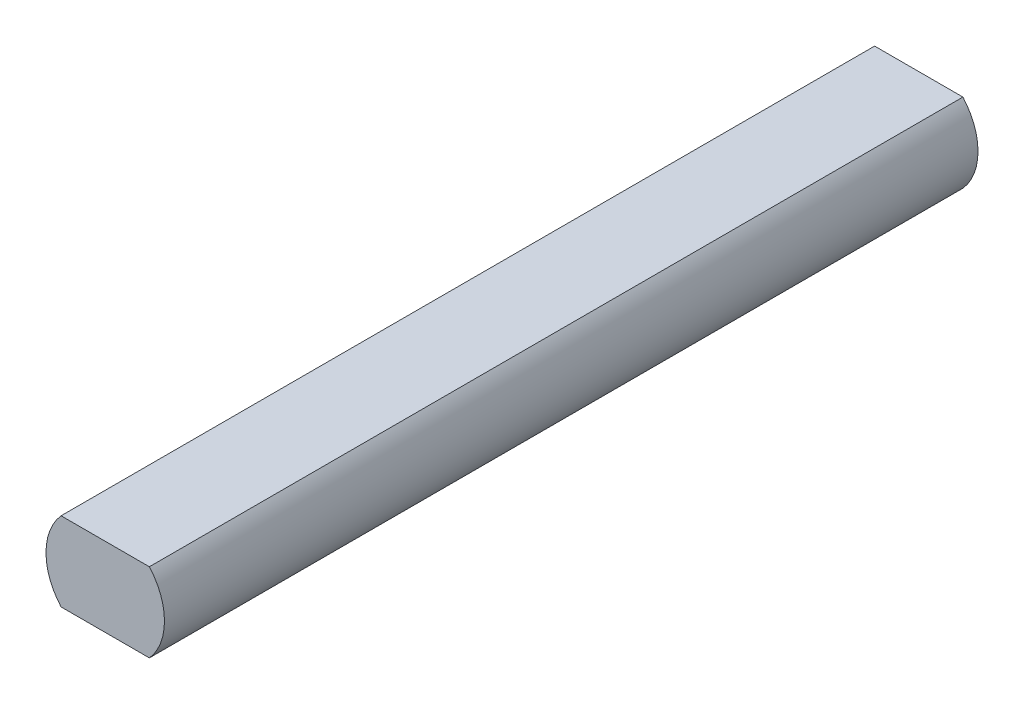
SolidWorks part; units mm, degrees
ref_plane "Front Plane" through (0, 0, 0) normal (0, 0, 1) x (1, 0, 0)
ref_plane "Top Plane" through (0, 0, 0) normal (0, 1, 0) x (1, 0, 0)
ref_plane "Right Plane" through (0, 0, 0) normal (1, 0, 0) x (0, 0, -1)
sketch "Sketch1" plane through (0, 0, 0) normal (0, 0, 1) x (1, 0, 0)
  line L0 (2.0092, 1.7967) -> (-2.0092, 1.7967)
  line L1 (-2.0092, -1.7967) -> (2.0092, -1.7967)
  arc A0 (-2.0092, -1.7967) -> (-2.0092, 1.7967) centre (0, 0) cw
  arc A1 (2.0092, 1.7967) -> (2.0092, -1.7967) centre (0, 0) cw
  circle A2 centre (0, 0) radius 2.6954 construction
  dimension "D2" = 5.3907
  dimension "D1" = 3.5933
extrude "Boss-Extrude1" add sketch "Sketch1" along normal mid plane 37.023
sketch "Sketch2" plane through (0, 0, 18.5115) normal (0, 0, 1) x (1, 0, 0)
  line L0 (-2.6954, 0) -> (2.6954, 0) construction
  line L1 (0, 2.6954) -> (0, -2.6954) construction
  arc A0 (-2.0092, 1.7967) -> (-2.0092, -1.7967) centre (0, 0) ccw construction
  arc A1 (2.0092, -1.7967) -> (2.0092, 1.7967) centre (0, 0) ccw construction
  circle A2 centre (0, 0) radius 2.6954 construction
equation "\"motor_thiccness\"= 18.773"
equation "\"axis\"= 18.25"
equation "\"D1@Boss-Extrude1\"=\"axis\"+\"motor_thiccness\""
